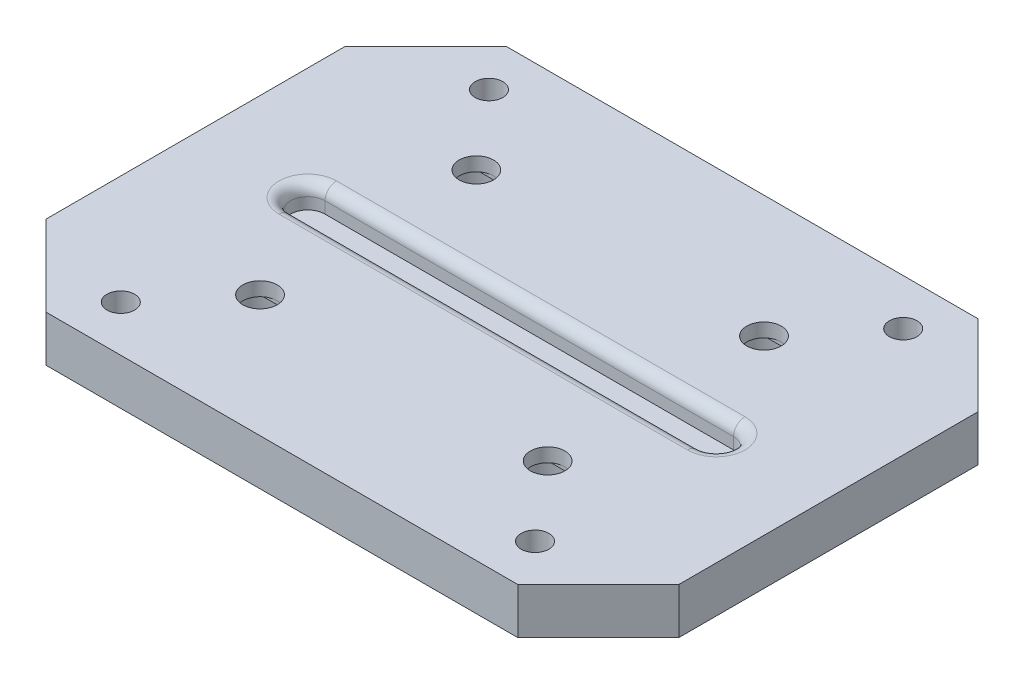
SolidWorks part; units mm, degrees
ref_plane "Front Plane" through (0, 0, 0) normal (0, 0, 1) x (1, 0, 0)
ref_plane "Top Plane" through (0, 0, 0) normal (0, 1, 0) x (1, 0, 0)
ref_plane "Right Plane" through (0, 0, 0) normal (1, 0, 0) x (0, 0, -1)
sketch "Sketch1" plane through (0, 0, 0) normal (0, 1, 0) x (1, 0, 0)
  line L2 (-82.8, -19) -> (-56.8, -19)
  line L3 (-56.8, -15) -> (-82.8, -15)
  line L4 (-82.8, -19) -> (-56.8, -19) construction
  line L5 (-56.8, -15) -> (-82.8, -15) construction
  line L6 (82.8, 19) -> (56.8, 19)
  line L7 (56.8, 15) -> (82.8, 15)
  line L8 (82.8, 19) -> (56.8, 19) construction
  line L9 (56.8, 15) -> (82.8, 15) construction
  line L10 (-82.8, 15) -> (-56.8, 15)
  line L11 (-56.8, 19) -> (-82.8, 19)
  line L12 (-51.9, 14.5) -> (-51.9, -14.5)
  line L13 (-50.4, -16) -> (-41.4, -16)
  line L14 (-39.9, -14.5) -> (-39.9, 14.5)
  line L15 (-41.4, 16) -> (-50.4, 16)
  line L16 (-51.9, 14.5) -> (-51.9, -14.5) construction
  line L17 (-50.4, -16) -> (-41.4, -16) construction
  line L18 (-39.9, -14.5) -> (-39.9, 14.5) construction
  line L19 (-41.4, 16) -> (-50.4, 16) construction
  line L20 (-82.8, 15) -> (-56.8, 15) construction
  line L21 (-56.8, 19) -> (-82.8, 19) construction
  line L22 (56.8, -19) -> (82.8, -19)
  line L23 (82.8, -15) -> (56.8, -15)
  line L24 (56.8, -19) -> (82.8, -19) construction
  line L25 (82.8, -15) -> (56.8, -15) construction
  line L26 (-12.5, -10.9) -> (12.5, -10.9)
  line L27 (12.5, -7.9) -> (-12.5, -7.9)
  line L28 (41.4, -16) -> (50.4, -16)
  line L29 (51.9, -14.5) -> (51.9, 14.5)
  line L30 (50.4, 16) -> (41.4, 16)
  line L31 (39.9, 14.5) -> (39.9, -14.5)
  line L32 (41.4, -16) -> (50.4, -16) construction
  line L33 (51.9, -14.5) -> (51.9, 14.5) construction
  line L34 (50.4, 16) -> (41.4, 16) construction
  line L35 (39.9, 14.5) -> (39.9, -14.5) construction
  line L36 (-12.5, -10.9) -> (12.5, -10.9)
  line L37 (12.5, -7.9) -> (-12.5, -7.9)
  line L38 (12.5, 10.9) -> (-12.5, 10.9)
  line L39 (-12.5, 7.9) -> (12.5, 7.9)
  line L40 (12.5, 10.9) -> (-12.5, 10.9)
  line L41 (-12.5, 7.9) -> (12.5, 7.9)
  line L42 (-17.75, -1.5) -> (17.75, -1.5)
  line L43 (17.75, 1.5) -> (-17.75, 1.5)
  line L44 (33.9411, 26.8701) -> (42.4264, 35.3553)
  line L45 (42.4264, 36.7696) -> (36.7696, 42.4264)
  line L46 (35.3553, 42.4264) -> (26.8701, 33.9411)
  line L47 (26.8701, 32.5269) -> (32.5269, 26.8701)
  line L48 (33.9411, 26.8701) -> (42.4264, 35.3553) construction
  line L49 (42.4264, 36.7696) -> (36.7696, 42.4264) construction
  line L50 (35.3553, 42.4264) -> (26.8701, 33.9411) construction
  line L51 (26.8701, 32.5269) -> (32.5269, 26.8701) construction
  line L52 (16, -48.35) -> (16, -39.35)
  line L53 (14.5, -37.85) -> (-14.5, -37.85)
  line L54 (-16, -39.35) -> (-16, -48.35)
  line L55 (-14.5, -49.85) -> (14.5, -49.85)
  line L56 (16, -48.35) -> (16, -39.35) construction
  line L57 (14.5, -37.85) -> (-14.5, -37.85) construction
  line L58 (-16, -39.35) -> (-16, -48.35) construction
  line L59 (-14.5, -49.85) -> (14.5, -49.85) construction
  line L60 (-36.7696, 42.4264) -> (-42.4264, 36.7696)
  line L61 (-42.4264, 35.3553) -> (-33.9411, 26.8701)
  line L62 (-32.5269, 26.8701) -> (-26.8701, 32.5269)
  line L63 (-26.8701, 33.9411) -> (-35.3553, 42.4264)
  line L64 (-36.7696, 42.4264) -> (-42.4264, 36.7696) construction
  line L65 (-42.4264, 35.3553) -> (-33.9411, 26.8701) construction
  line L66 (-32.5269, 26.8701) -> (-26.8701, 32.5269) construction
  line L67 (-26.8701, 33.9411) -> (-35.3553, 42.4264) construction
  line L68 (16, 39.35) -> (16, 48.35)
  line L69 (14.5, 49.85) -> (-14.5, 49.85)
  line L70 (-16, 48.35) -> (-16, 39.35)
  line L71 (-14.5, 37.85) -> (14.5, 37.85)
  line L72 (16, 39.35) -> (16, 48.35) construction
  line L73 (14.5, 49.85) -> (-14.5, 49.85) construction
  line L74 (-16, 48.35) -> (-16, 39.35) construction
  line L75 (-14.5, 37.85) -> (14.5, 37.85) construction
  line L76 (26.8701, -33.9411) -> (35.3553, -42.4264)
  line L77 (36.7696, -42.4264) -> (42.4264, -36.7696)
  line L78 (42.4264, -35.3553) -> (33.9411, -26.8701)
  line L79 (32.5269, -26.8701) -> (26.8701, -32.5269)
  line L80 (26.8701, -33.9411) -> (35.3553, -42.4264) construction
  line L81 (36.7696, -42.4264) -> (42.4264, -36.7696) construction
  line L82 (42.4264, -35.3553) -> (33.9411, -26.8701) construction
  line L83 (32.5269, -26.8701) -> (26.8701, -32.5269) construction
  line L84 (-17.75, -1.5) -> (17.75, -1.5)
  line L85 (17.75, 1.5) -> (-17.75, 1.5)
  line L88 (-42.4264, -36.7696) -> (-36.7696, -42.4264)
  line L89 (-35.3553, -42.4264) -> (-26.8701, -33.9411)
  line L90 (-26.8701, -32.5269) -> (-32.5269, -26.8701)
  line L91 (-33.9411, -26.8701) -> (-42.4264, -35.3553)
  line L92 (-42.4264, -36.7696) -> (-36.7696, -42.4264) construction
  line L93 (-35.3553, -42.4264) -> (-26.8701, -33.9411) construction
  line L94 (-26.8701, -32.5269) -> (-32.5269, -26.8701) construction
  line L95 (-33.9411, -26.8701) -> (-42.4264, -35.3553) construction
  line L116 (-30.1457, 57.5355) -> (-57.5168, 30.1645)
  line L117 (-26.6102, 59) -> (-30.1457, 57.5355)
  line L118 (26.6102, 59) -> (-26.6102, 59)
  line L119 (30.1457, 57.5355) -> (26.6102, 59)
  line L120 (57.5168, 30.1645) -> (30.1457, 57.5355)
  line L121 (61.0523, 28.7) -> (57.5168, 30.1645)
  line L122 (85.8, 28.7) -> (61.0523, 28.7)
  line L123 (90.8, 23.7) -> (85.8, 28.7)
  line L124 (90.8, -23.7) -> (90.8, 23.7)
  line L125 (85.8, -28.7) -> (90.8, -23.7)
  line L126 (61.0523, -28.7) -> (85.8, -28.7)
  line L127 (57.5168, -30.1645) -> (61.0523, -28.7)
  line L128 (30.1457, -57.5355) -> (57.5168, -30.1645)
  line L129 (26.6102, -59) -> (30.1457, -57.5355)
  line L130 (-26.6102, -59) -> (26.6102, -59)
  line L131 (-30.1457, -57.5355) -> (-26.6102, -59)
  line L132 (-57.5168, -30.1645) -> (-30.1457, -57.5355)
  line L133 (-61.0523, -28.7) -> (-57.5168, -30.1645)
  line L134 (-85.8, -28.7) -> (-61.0523, -28.7)
  line L135 (-90.8, -23.7) -> (-85.8, -28.7)
  line L136 (-90.8, 23.7) -> (-90.8, -23.7)
  line L137 (-85.8, 28.7) -> (-90.8, 23.7)
  line L138 (-61.0523, 28.7) -> (-85.8, 28.7)
  line L139 (-57.5168, 30.1645) -> (-61.0523, 28.7)
  line L140 (-30.1457, 57.5355) -> (-57.5168, 30.1645) construction
  line L141 (-26.6102, 59) -> (-30.1457, 57.5355) construction
  line L142 (26.6102, 59) -> (-26.6102, 59) construction
  line L143 (30.1457, 57.5355) -> (26.6102, 59) construction
  line L144 (57.5168, 30.1645) -> (30.1457, 57.5355) construction
  line L145 (61.0523, 28.7) -> (57.5168, 30.1645) construction
  line L146 (85.8, 28.7) -> (61.0523, 28.7) construction
  line L147 (90.8, 23.7) -> (85.8, 28.7) construction
  line L148 (90.8, -23.7) -> (90.8, 23.7) construction
  line L149 (85.8, -28.7) -> (90.8, -23.7) construction
  line L150 (61.0523, -28.7) -> (85.8, -28.7) construction
  line L151 (57.5168, -30.1645) -> (61.0523, -28.7) construction
  line L152 (30.1457, -57.5355) -> (57.5168, -30.1645) construction
  line L153 (26.6102, -59) -> (30.1457, -57.5355) construction
  line L154 (-26.6102, -59) -> (26.6102, -59) construction
  line L155 (-30.1457, -57.5355) -> (-26.6102, -59) construction
  line L156 (-57.5168, -30.1645) -> (-30.1457, -57.5355) construction
  line L157 (-61.0523, -28.7) -> (-57.5168, -30.1645) construction
  line L158 (-85.8, -28.7) -> (-61.0523, -28.7) construction
  line L159 (-90.8, -23.7) -> (-85.8, -28.7) construction
  line L160 (-90.8, 23.7) -> (-90.8, -23.7) construction
  line L161 (-85.8, 28.7) -> (-90.8, 23.7) construction
  line L162 (-61.0523, 28.7) -> (-85.8, 28.7) construction
  line L163 (-57.5168, 30.1645) -> (-61.0523, 28.7) construction
  circle A1 centre (-33.234, 47.3762) radius 1.6
  arc A2 (-56.8, -19) -> (-56.8, -15) centre (-56.8, -17) ccw
  arc A3 (-82.8, -15) -> (-82.8, -19) centre (-82.8, -17) ccw
  arc A4 (-56.8, -19) -> (-56.8, -15) centre (-56.8, -17) ccw construction
  arc A5 (-82.8, -15) -> (-82.8, -19) centre (-82.8, -17) ccw construction
  arc A6 (56.8, 19) -> (56.8, 15) centre (56.8, 17) ccw
  arc A7 (82.8, 15) -> (82.8, 19) centre (82.8, 17) ccw
  arc A8 (56.8, 19) -> (56.8, 15) centre (56.8, 17) ccw construction
  arc A9 (82.8, 15) -> (82.8, 19) centre (82.8, 17) ccw construction
  arc A10 (-56.8, 15) -> (-56.8, 19) centre (-56.8, 17) ccw
  arc A11 (-82.8, 19) -> (-82.8, 15) centre (-82.8, 17) ccw
  arc A12 (-51.9, -14.5) -> (-50.4, -16) centre (-50.4, -14.5) ccw
  arc A13 (-41.4, -16) -> (-39.9, -14.5) centre (-41.4, -14.5) ccw
  arc A14 (-39.9, 14.5) -> (-41.4, 16) centre (-41.4, 14.5) ccw
  arc A15 (-50.4, 16) -> (-51.9, 14.5) centre (-50.4, 14.5) ccw
  arc A16 (-51.9, -14.5) -> (-50.4, -16) centre (-50.4, -14.5) ccw construction
  arc A17 (-41.4, -16) -> (-39.9, -14.5) centre (-41.4, -14.5) ccw construction
  arc A18 (-39.9, 14.5) -> (-41.4, 16) centre (-41.4, 14.5) ccw construction
  arc A19 (-50.4, 16) -> (-51.9, 14.5) centre (-50.4, 14.5) ccw construction
  arc A20 (-56.8, 15) -> (-56.8, 19) centre (-56.8, 17) ccw construction
  arc A21 (-82.8, 19) -> (-82.8, 15) centre (-82.8, 17) ccw construction
  arc A22 (82.8, -19) -> (82.8, -15) centre (82.8, -17) ccw
  arc A23 (56.8, -15) -> (56.8, -19) centre (56.8, -17) ccw
  arc A24 (82.8, -19) -> (82.8, -15) centre (82.8, -17) ccw construction
  arc A25 (56.8, -15) -> (56.8, -19) centre (56.8, -17) ccw construction
  arc A26 (12.5, -10.9) -> (12.5, -7.9) centre (12.5, -9.4) ccw
  arc A27 (-12.5, -7.9) -> (-12.5, -10.9) centre (-12.5, -9.4) ccw
  arc A28 (50.4, -16) -> (51.9, -14.5) centre (50.4, -14.5) ccw
  arc A29 (51.9, 14.5) -> (50.4, 16) centre (50.4, 14.5) ccw
  arc A30 (41.4, 16) -> (39.9, 14.5) centre (41.4, 14.5) ccw
  arc A31 (39.9, -14.5) -> (41.4, -16) centre (41.4, -14.5) ccw
  arc A32 (50.4, -16) -> (51.9, -14.5) centre (50.4, -14.5) ccw construction
  arc A33 (51.9, 14.5) -> (50.4, 16) centre (50.4, 14.5) ccw construction
  arc A34 (41.4, 16) -> (39.9, 14.5) centre (41.4, 14.5) ccw construction
  arc A35 (39.9, -14.5) -> (41.4, -16) centre (41.4, -14.5) ccw construction
  arc A36 (12.5, -10.9) -> (12.5, -7.9) centre (12.5, -9.4) ccw
  arc A37 (-12.5, -7.9) -> (-12.5, -10.9) centre (-12.5, -9.4) ccw
  arc A38 (-12.5, 10.9) -> (-12.5, 7.9) centre (-12.5, 9.4) ccw
  arc A39 (12.5, 7.9) -> (12.5, 10.9) centre (12.5, 9.4) ccw
  arc A40 (-12.5, 10.9) -> (-12.5, 7.9) centre (-12.5, 9.4) ccw
  arc A41 (12.5, 7.9) -> (12.5, 10.9) centre (12.5, 9.4) ccw
  circle A42 centre (-33.234, 47.3762) radius 1.6 construction
  circle A43 centre (33.234, 47.3762) radius 1.6
  arc A44 (42.4264, 35.3553) -> (42.4264, 36.7696) centre (41.7193, 36.0624) ccw
  arc A45 (36.7696, 42.4264) -> (35.3553, 42.4264) centre (36.0624, 41.7193) ccw
  arc A46 (26.8701, 33.9411) -> (26.8701, 32.5269) centre (27.5772, 33.234) ccw
  arc A47 (32.5269, 26.8701) -> (33.9411, 26.8701) centre (33.234, 27.5772) ccw
  arc A48 (42.4264, 35.3553) -> (42.4264, 36.7696) centre (41.7193, 36.0624) ccw construction
  arc A49 (36.7696, 42.4264) -> (35.3553, 42.4264) centre (36.0624, 41.7193) ccw construction
  arc A50 (26.8701, 33.9411) -> (26.8701, 32.5269) centre (27.5772, 33.234) ccw construction
  arc A51 (32.5269, 26.8701) -> (33.9411, 26.8701) centre (33.234, 27.5772) ccw construction
  arc A52 (16, -39.35) -> (14.5, -37.85) centre (14.5, -39.35) ccw
  arc A53 (-14.5, -37.85) -> (-16, -39.35) centre (-14.5, -39.35) ccw
  arc A54 (-16, -48.35) -> (-14.5, -49.85) centre (-14.5, -48.35) ccw
  arc A55 (14.5, -49.85) -> (16, -48.35) centre (14.5, -48.35) ccw
  arc A56 (16, -39.35) -> (14.5, -37.85) centre (14.5, -39.35) ccw construction
  arc A57 (-14.5, -37.85) -> (-16, -39.35) centre (-14.5, -39.35) ccw construction
  arc A58 (-16, -48.35) -> (-14.5, -49.85) centre (-14.5, -48.35) ccw construction
  arc A59 (14.5, -49.85) -> (16, -48.35) centre (14.5, -48.35) ccw construction
  arc A60 (-42.4264, 36.7696) -> (-42.4264, 35.3553) centre (-41.7193, 36.0624) ccw
  arc A61 (-33.9411, 26.8701) -> (-32.5269, 26.8701) centre (-33.234, 27.5772) ccw
  arc A62 (-26.8701, 32.5269) -> (-26.8701, 33.9411) centre (-27.5772, 33.234) ccw
  arc A63 (-35.3553, 42.4264) -> (-36.7696, 42.4264) centre (-36.0624, 41.7193) ccw
  arc A64 (-42.4264, 36.7696) -> (-42.4264, 35.3553) centre (-41.7193, 36.0624) ccw construction
  arc A65 (-33.9411, 26.8701) -> (-32.5269, 26.8701) centre (-33.234, 27.5772) ccw construction
  arc A66 (-26.8701, 32.5269) -> (-26.8701, 33.9411) centre (-27.5772, 33.234) ccw construction
  arc A67 (-35.3553, 42.4264) -> (-36.7696, 42.4264) centre (-36.0624, 41.7193) ccw construction
  arc A68 (16, 48.35) -> (14.5, 49.85) centre (14.5, 48.35) ccw
  arc A69 (-14.5, 49.85) -> (-16, 48.35) centre (-14.5, 48.35) ccw
  arc A70 (-16, 39.35) -> (-14.5, 37.85) centre (-14.5, 39.35) ccw
  arc A71 (14.5, 37.85) -> (16, 39.35) centre (14.5, 39.35) ccw
  arc A72 (16, 48.35) -> (14.5, 49.85) centre (14.5, 48.35) ccw construction
  arc A73 (-14.5, 49.85) -> (-16, 48.35) centre (-14.5, 48.35) ccw construction
  arc A74 (-16, 39.35) -> (-14.5, 37.85) centre (-14.5, 39.35) ccw construction
  arc A75 (14.5, 37.85) -> (16, 39.35) centre (14.5, 39.35) ccw construction
  arc A76 (35.3553, -42.4264) -> (36.7696, -42.4264) centre (36.0624, -41.7193) ccw
  arc A77 (42.4264, -36.7696) -> (42.4264, -35.3553) centre (41.7193, -36.0624) ccw
  arc A78 (33.9411, -26.8701) -> (32.5269, -26.8701) centre (33.234, -27.5772) ccw
  arc A79 (26.8701, -32.5269) -> (26.8701, -33.9411) centre (27.5772, -33.234) ccw
  arc A80 (35.3553, -42.4264) -> (36.7696, -42.4264) centre (36.0624, -41.7193) ccw construction
  arc A81 (42.4264, -36.7696) -> (42.4264, -35.3553) centre (41.7193, -36.0624) ccw construction
  arc A82 (33.9411, -26.8701) -> (32.5269, -26.8701) centre (33.234, -27.5772) ccw construction
  arc A83 (26.8701, -32.5269) -> (26.8701, -33.9411) centre (27.5772, -33.234) ccw construction
  circle A84 centre (33.234, 47.3762) radius 1.6 construction
  circle A85 centre (47.3762, 33.234) radius 1.6
  circle A86 centre (47.3762, 33.234) radius 1.6 construction
  circle A87 centre (47.3762, -33.234) radius 1.6
  arc A88 (17.75, -1.5) -> (17.75, 1.5) centre (17.75, 0) ccw
  arc A89 (-17.75, 1.5) -> (-17.75, -1.5) centre (-17.75, 0) ccw
  arc A90 (17.75, -1.5) -> (17.75, 1.5) centre (17.75, 0) ccw
  arc A91 (-17.75, 1.5) -> (-17.75, -1.5) centre (-17.75, 0) ccw
  circle A92 centre (47.3762, -33.234) radius 1.6 construction
  circle A93 centre (33.234, -47.3762) radius 1.6
  arc A94 (-36.7696, -42.4264) -> (-35.3553, -42.4264) centre (-36.0624, -41.7193) ccw
  arc A95 (-26.8701, -33.9411) -> (-26.8701, -32.5269) centre (-27.5772, -33.234) ccw
  arc A96 (-32.5269, -26.8701) -> (-33.9411, -26.8701) centre (-33.234, -27.5772) ccw
  arc A97 (-42.4264, -35.3553) -> (-42.4264, -36.7696) centre (-41.7193, -36.0624) ccw
  arc A98 (-36.7696, -42.4264) -> (-35.3553, -42.4264) centre (-36.0624, -41.7193) ccw construction
  arc A99 (-26.8701, -33.9411) -> (-26.8701, -32.5269) centre (-27.5772, -33.234) ccw construction
  arc A100 (-32.5269, -26.8701) -> (-33.9411, -26.8701) centre (-33.234, -27.5772) ccw construction
  arc A101 (-42.4264, -35.3553) -> (-42.4264, -36.7696) centre (-41.7193, -36.0624) ccw construction
  circle A102 centre (33.234, -47.3762) radius 1.6 construction
  circle A103 centre (-33.234, -47.3762) radius 1.6
  circle A104 centre (-33.234, -47.3762) radius 1.6 construction
  circle A105 centre (-47.3762, -33.234) radius 1.6
  circle A106 centre (-47.3762, -33.234) radius 1.6 construction
  circle A107 centre (-47.3762, 33.234) radius 1.6
  circle A108 centre (-47.3762, 33.234) radius 1.6 construction
  dimension "D1" = 0
  dimension "D2" = 0
  dimension "D3" = 0
  dimension "D4" = 0
  dimension "D5" = 0
  dimension "D6" = 0
  dimension "D7" = 0
  dimension "D8" = 0
  dimension "D9" = 0
  dimension "D10" = 0
  dimension "D11" = 0
  dimension "D12" = 0
  dimension "D13" = 0
  dimension "D14" = 0
  dimension "D15" = 0
  dimension "D16" = 0
  dimension "D17" = 0
  dimension "D18" = 0
  dimension "D19" = 0
  dimension "D20" = 0
  dimension "D21" = 0
  dimension "D22" = 0
  dimension "D23" = 0
  dimension "D24" = 0
sketch "Sketch2" plane through (0, 0, 0) normal (0, 1, 0) x (1, 0, 0)
  line L0 (0, -14) -> (0, 14) construction
  line L1 (-904.7843, 14) -> (44334.4284, 14) construction
  line L2 (-910.7454, -14) -> (44328.4673, -14) construction
  line L3 (-16, 0) -> (16, 0) construction
  line L4 (16, -904.7843) -> (16, 44334.4284) construction
  line L5 (-16, -896.2279) -> (-16, 44342.9847) construction
  line L7 (-27.5, -20) -> (27.5, -20)
  line L8 (-27.5, -20) -> (-27.5, 20)
  line L9 (-27.5, 20) -> (27.5, 20)
  line L10 (27.5, -20) -> (27.5, 20)
  line L11 (-27.5, -20) -> (27.5, 20) construction
  line L12 (-27.5, 20) -> (27.5, -20) construction
  line L14 (12.5, 10.9) -> (-12.5, 10.9)
  line L15 (-12.5, 7.9) -> (12.5, 7.9)
  line L16 (12.5, 10.9) -> (-12.5, 10.9) construction
  line L17 (-12.5, 7.9) -> (12.5, 7.9) construction
  line L18 (12.5, -7.9) -> (-12.5, -7.9)
  line L19 (-12.5, -10.9) -> (12.5, -10.9)
  line L20 (12.5, -7.9) -> (-12.5, -7.9) construction
  line L21 (-12.5, -10.9) -> (12.5, -10.9) construction
  line L22 (17.75, 1.5) -> (-17.75, 1.5)
  line L23 (-17.75, -1.5) -> (17.75, -1.5)
  line L24 (17.75, 1.5) -> (-17.75, 1.5) construction
  line L25 (-17.75, -1.5) -> (17.75, -1.5) construction
  circle A0 centre (18, 16) radius 2 construction
  circle A1 centre (-18, 16) radius 2 construction
  circle A2 centre (-18, -16) radius 2 construction
  circle A3 centre (18, -16) radius 2 construction
  circle A4 centre (-18, -16) radius 1.2
  circle A5 centre (18, -16) radius 1.2
  arc A6 (-12.5, 10.9) -> (-12.5, 7.9) centre (-12.5, 9.4) ccw
  arc A7 (12.5, 7.9) -> (12.5, 10.9) centre (12.5, 9.4) ccw
  arc A8 (-12.5, 10.9) -> (-12.5, 7.9) centre (-12.5, 9.4) ccw construction
  arc A9 (12.5, 7.9) -> (12.5, 10.9) centre (12.5, 9.4) ccw construction
  arc A10 (-12.5, -7.9) -> (-12.5, -10.9) centre (-12.5, -9.4) ccw
  arc A11 (12.5, -10.9) -> (12.5, -7.9) centre (12.5, -9.4) ccw
  arc A12 (-12.5, -7.9) -> (-12.5, -10.9) centre (-12.5, -9.4) ccw construction
  arc A13 (12.5, -10.9) -> (12.5, -7.9) centre (12.5, -9.4) ccw construction
  arc A14 (-17.75, 1.5) -> (-17.75, -1.5) centre (-17.75, 0) ccw
  arc A15 (17.75, -1.5) -> (17.75, 1.5) centre (17.75, 0) ccw
  arc A16 (-17.75, 1.5) -> (-17.75, -1.5) centre (-17.75, 0) ccw construction
  arc A17 (17.75, -1.5) -> (17.75, 1.5) centre (17.75, 0) ccw construction
  circle A18 centre (-18, 16) radius 1.2
  circle A19 centre (18, 16) radius 1.2
  point P2 (0, 0)
  point P10 (0, 0)
  point P23 (0, 0)
  dimension "D3" = 4
  dimension "D9" = 2.4
  dimension "D1" = 32
  dimension "D2" = 28
  dimension "D4" = 55
  dimension "D5" = 40
  dimension "D6" = 0
  dimension "D7" = 0
  dimension "D8" = 0
extrude "Boss-Extrude1" add sketch "Sketch2" against normal blind 4
chamfer "Chamfer1" distance 7 angle 45 4 edges at (-27.5, -2, 20) (27.5, -2, 20) (27.5, -2, -20) (-27.5, -2, -20)
ref_plane "Plane1" through (0, -2, 0) normal (0, 1, 0) x (1, 0, 0)
sketch "Sketch3" plane through (0, -2, 0) normal (0, 1, 0) x (1, 0, 0)
  line L2 (12.5, 10.9) -> (-12.5, 10.9)
  line L3 (-12.5, 7.9) -> (12.5, 7.9)
  line L4 (12.5, 10.9) -> (-12.5, 10.9) construction
  line L5 (-12.5, 7.9) -> (12.5, 7.9) construction
  line L6 (-12.5, -10.9) -> (12.5, -10.9)
  line L7 (12.5, -7.9) -> (-12.5, -7.9)
  line L8 (-12.5, -10.9) -> (12.5, -10.9) construction
  line L9 (12.5, -7.9) -> (-12.5, -7.9) construction
  line L10 (17.75, 1.5) -> (-17.75, 1.5)
  line L11 (-17.75, -1.5) -> (17.75, -1.5)
  line L12 (17.75, 1.5) -> (-17.75, 1.5)
  line L13 (-17.75, -1.5) -> (17.75, -1.5)
  circle A0 centre (12.5, 9.4) radius 1.5
  circle A1 centre (-12.5, 9.4) radius 1.5
  arc A2 (-12.5, 10.9) -> (-12.5, 7.9) centre (-12.5, 9.4) ccw
  arc A3 (12.5, 7.9) -> (12.5, 10.9) centre (12.5, 9.4) ccw
  arc A4 (-12.5, 10.9) -> (-12.5, 7.9) centre (-12.5, 9.4) ccw construction
  arc A5 (12.5, 7.9) -> (12.5, 10.9) centre (12.5, 9.4) ccw construction
  arc A6 (12.5, -10.9) -> (12.5, -7.9) centre (12.5, -9.4) ccw
  arc A7 (-12.5, -7.9) -> (-12.5, -10.9) centre (-12.5, -9.4) ccw
  arc A8 (12.5, -10.9) -> (12.5, -7.9) centre (12.5, -9.4) ccw construction
  arc A9 (-12.5, -7.9) -> (-12.5, -10.9) centre (-12.5, -9.4) ccw construction
  arc A10 (17.75, -1.5) -> (17.75, 1.5) centre (17.75, 0) ccw
  arc A11 (-17.75, 1.5) -> (-17.75, -1.5) centre (-17.75, 0) ccw
  arc A12 (17.75, -1.5) -> (17.75, 1.5) centre (17.75, 0) ccw
  arc A13 (-17.75, 1.5) -> (-17.75, -1.5) centre (-17.75, 0) ccw
  circle A14 centre (-12.5, -9.4) radius 1.5
  circle A15 centre (12.5, -9.4) radius 1.5
  dimension "D4" = 3
  dimension "D1" = 0
  dimension "D2" = 0
  dimension "D3" = 0
extrude "Cut-Extrude1" cut sketch "Sketch3" along normal through all
fillet "Fillet1" radius 1 4 edges at (19.25, 0, 0) (0, 0, 1.5) (-19.25, 0, 0) (0, 0, -1.5)
sketch "Sketch4" plane through (0, -2, 0) normal (0, 1, 0) x (1, 0, 0)
  line L2 (12.5, 10.9) -> (-12.5, 10.9)
  line L3 (-12.5, 7.9) -> (12.5, 7.9)
  line L4 (12.5, 10.9) -> (-12.5, 10.9) construction
  line L5 (-12.5, 7.9) -> (12.5, 7.9) construction
  line L6 (-12.5, -10.9) -> (12.5, -10.9)
  line L7 (12.5, -7.9) -> (-12.5, -7.9)
  line L8 (-12.5, -10.9) -> (12.5, -10.9) construction
  line L9 (12.5, -7.9) -> (-12.5, -7.9) construction
  line L10 (17.75, 1.5) -> (-17.75, 1.5)
  line L11 (-17.75, -1.5) -> (17.75, -1.5)
  line L12 (17.75, 1.5) -> (-17.75, 1.5) construction
  line L13 (-17.75, -1.5) -> (17.75, -1.5) construction
  circle A0 centre (-12.5, 9.4) radius 2.5
  circle A1 centre (12.5, 9.4) radius 2.5
  arc A2 (-12.5, 10.9) -> (-12.5, 7.9) centre (-12.5, 9.4) ccw
  arc A3 (12.5, 7.9) -> (12.5, 10.9) centre (12.5, 9.4) ccw
  arc A4 (-12.5, 10.9) -> (-12.5, 7.9) centre (-12.5, 9.4) ccw construction
  arc A5 (12.5, 7.9) -> (12.5, 10.9) centre (12.5, 9.4) ccw construction
  arc A6 (12.5, -10.9) -> (12.5, -7.9) centre (12.5, -9.4) ccw
  arc A7 (-12.5, -7.9) -> (-12.5, -10.9) centre (-12.5, -9.4) ccw
  arc A8 (12.5, -10.9) -> (12.5, -7.9) centre (12.5, -9.4) ccw construction
  arc A9 (-12.5, -7.9) -> (-12.5, -10.9) centre (-12.5, -9.4) ccw construction
  arc A10 (17.75, -1.5) -> (17.75, 1.5) centre (17.75, 0) ccw
  arc A11 (-17.75, 1.5) -> (-17.75, -1.5) centre (-17.75, 0) ccw
  arc A12 (17.75, -1.5) -> (17.75, 1.5) centre (17.75, 0) ccw construction
  arc A13 (-17.75, 1.5) -> (-17.75, -1.5) centre (-17.75, 0) ccw construction
  circle A14 centre (-12.5, -9.4) radius 2.5
  circle A15 centre (12.5, -9.4) radius 2.5
  dimension "D4" = 5
  dimension "D1" = 0
  dimension "D2" = 0
  dimension "D3" = 0
extrude "Cut-Extrude2" cut sketch "Sketch4" against normal through all from offset 0.5
sketch "Sketch5" plane through (0, -1.5, 0) normal (0, 1, 0) x (1, 0, 0)
  line L0 (-14.5, -10.9) -> (-10.5, -10.9)
  line L1 (-14.5, -7.9) -> (-10.5, -7.9)
  line L2 (-14.5, 7.9) -> (-10.5, 7.9)
  line L3 (-14.5, 10.9) -> (-10.5, 10.9)
  line L4 (10.5, -10.9) -> (14.5, -10.9)
  line L5 (10.5, -7.9) -> (14.5, -7.9)
  line L6 (10.5, 7.9) -> (14.5, 7.9)
  line L7 (10.5, 10.9) -> (14.5, 10.9)
  circle A0 centre (-12.5, -9.4) radius 1.5 construction
  circle A1 centre (-12.5, 9.4) radius 2.5
  arc A2 (-14.5, 10.9) -> (-14.5, 7.9) centre (-12.5, 9.4) ccw
  circle A3 centre (12.5, -9.4) radius 2.5
  arc A4 (10.5, -7.9) -> (10.5, -10.9) centre (12.5, -9.4) ccw
  circle A5 centre (-12.5, -9.4) radius 2.5
  arc A6 (-10.5, -10.9) -> (-10.5, -7.9) centre (-12.5, -9.4) ccw
  circle A7 centre (12.5, 9.4) radius 2.5
  arc A8 (14.5, 7.9) -> (14.5, 10.9) centre (12.5, 9.4) ccw
  circle A9 centre (12.5, -9.4) radius 1.5 construction
  circle A10 centre (12.5, 9.4) radius 1.5 construction
  circle A11 centre (-12.5, 9.4) radius 1.5 construction
  arc A12 (-14.5, -7.9) -> (-14.5, -10.9) centre (-12.5, -9.4) ccw
  arc A13 (14.5, -10.9) -> (14.5, -7.9) centre (12.5, -9.4) ccw
  arc A14 (-10.5, 7.9) -> (-10.5, 10.9) centre (-12.5, 9.4) ccw
  arc A15 (10.5, 10.9) -> (10.5, 7.9) centre (12.5, 9.4) ccw
  dimension "D1" = 0
  dimension "D2" = 0
  dimension "D3" = 0
  dimension "D4" = 0
extrude "Cut-Extrude6" cut sketch "Sketch5" along normal blind 0.3
